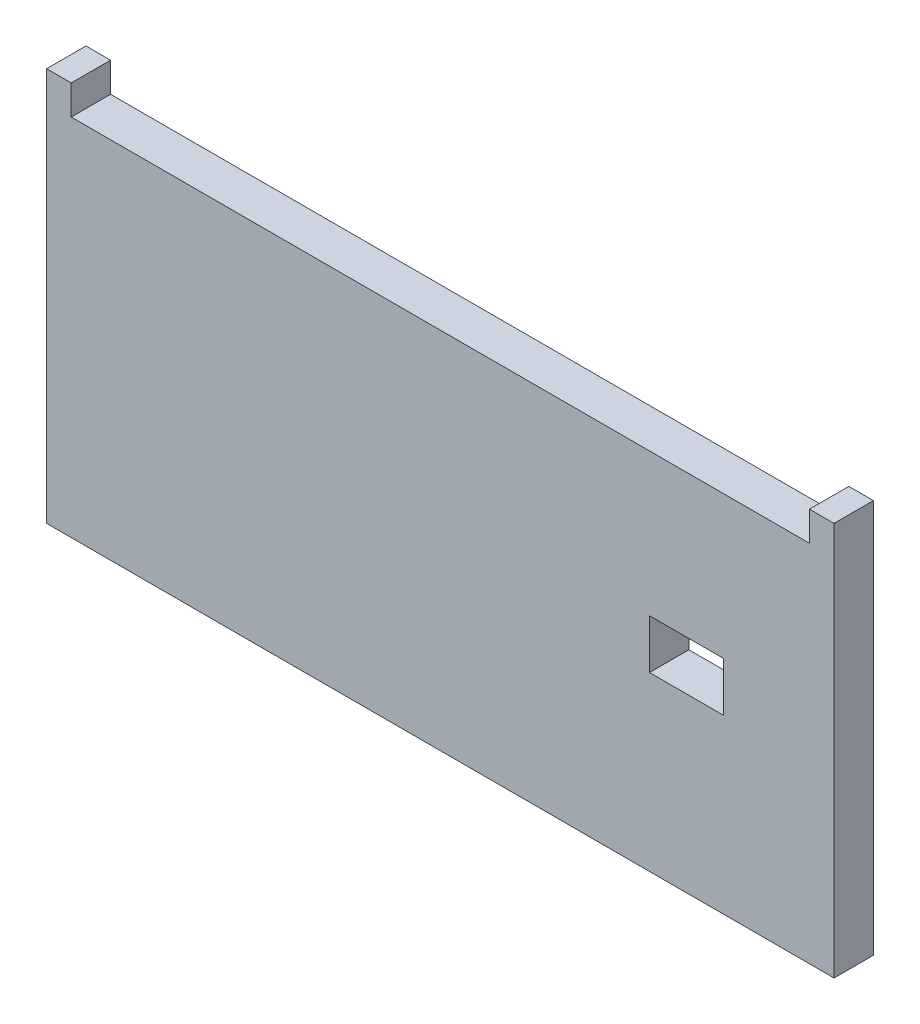
SolidWorks part; units mm, degrees
ref_plane "前视基准面" through (0, 0, 0) normal (0, 0, 1) x (1, 0, 0)
ref_plane "上视基准面" through (0, 0, 0) normal (0, 1, 0) x (1, 0, 0)
ref_plane "右视基准面" through (0, 0, 0) normal (1, 0, 0) x (0, 0, -1)
other "Configuration Table"
sketch "草图1" plane through (0, 0, 0) normal (0, 0, 1) x (1, 0, 0)
  line L1 (-80, -40) -> (80, -40)
  line L2 (-80, -40) -> (-80, 40)
  line L3 (-80, 40) -> (80, 40)
  line L4 (80, -40) -> (80, 40)
  line L5 (-80, -40) -> (80, 40) construction
  line L6 (-80, 40) -> (80, -40) construction
  point P0 (0, 0)
extrude "凸台-拉伸1" add sketch "草图1" along normal blind 8
sketch "草图2" plane through (0, 40, 0) normal (0, 1, 0) x (1, 0, 0)
  line L1 (-75, -37.5) -> (75, -37.5)
  line L2 (-75, -37.5) -> (-75, 37.5)
  line L3 (-75, 37.5) -> (75, 37.5)
  line L4 (75, -37.5) -> (75, 37.5)
  line L5 (-75, -37.5) -> (75, 37.5) construction
  line L6 (-75, 37.5) -> (75, -37.5) construction
  point P0 (0, 0)
extrude "切除-拉伸1" cut sketch "草图2" against normal blind 6
sketch "草图3" plane through (0, 0, 8) normal (0, 0, 1) x (1, 0, 0)
  line L1 (42.5, -5) -> (57.5, -5)
  line L2 (42.5, -5) -> (42.5, 5)
  line L3 (42.5, 5) -> (57.5, 5)
  line L4 (57.5, -5) -> (57.5, 5)
  line L5 (42.5, -5) -> (57.5, 5) construction
  line L6 (42.5, 5) -> (57.5, -5) construction
  point P0 (50, 0)
extrude "切除-拉伸2" cut sketch "草图3" against normal through all
